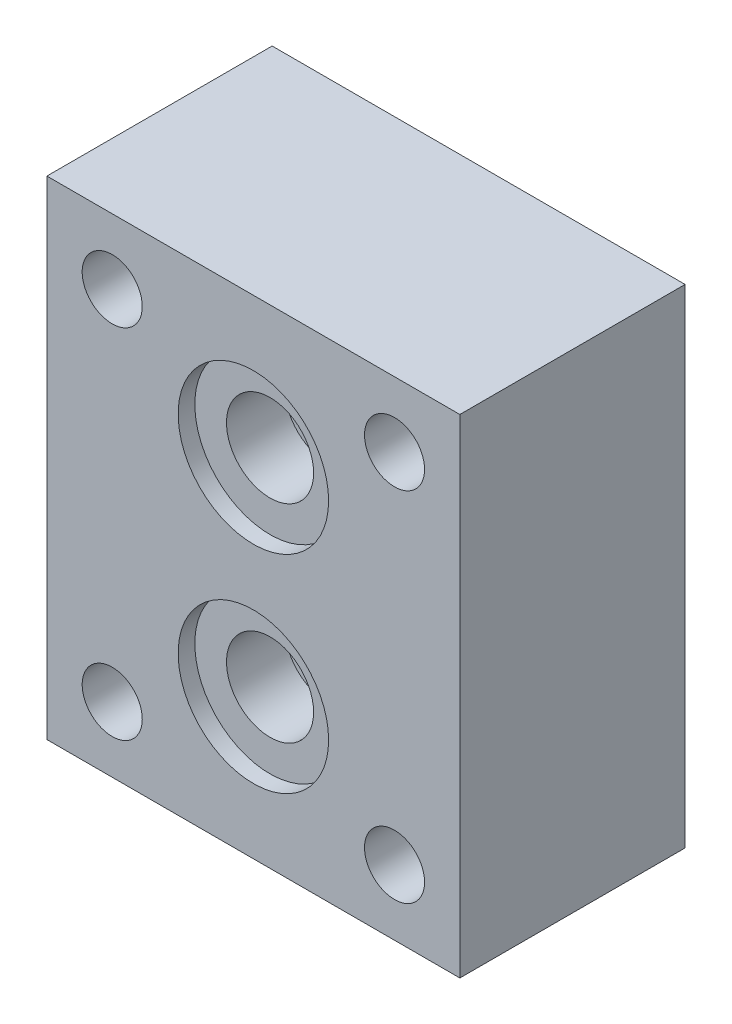
SolidWorks part; units mm, degrees
ref_plane "Front Plane" through (0, 0, 0) normal (1, 0, 0) x (0, 1, 0)
ref_plane "Top Plane" through (0, 0, 0) normal (0, 0, 1) x (0, 1, 0)
ref_plane "Right Plane" through (0, 0, 0) normal (0, 1, 0) x (-1, 0, 0)
sketch "Sketch1" plane through (0, 0, 0) normal (0, 0, 1) x (0, 1, 0)
  line L1 (-41.275, -34.925) -> (41.275, -34.925)
  line L2 (-41.275, -34.925) -> (-41.275, 34.925)
  line L3 (-41.275, 34.925) -> (41.275, 34.925)
  line L4 (41.275, -34.925) -> (41.275, 34.925)
  line L5 (-41.275, -34.925) -> (41.275, 34.925) construction
  line L6 (-41.275, 34.925) -> (41.275, -34.925) construction
  point P0 (0, 0)
  dimension "D1" = 41.275
  dimension "D2" = 34.925
extrude "Boss-Extrude1" add sketch "Sketch1" along normal mid plane 38.1
sketch "Sketch2" plane through (0, 0, 0) normal (0, 0, 1) x (0, 1, 0)
  circle A0 centre (-30.226, -23.876) radius 5.08
  circle A1 centre (30.226, -23.876) radius 5.08
  circle A2 centre (-30.226, 23.876) radius 5.08
  circle A3 centre (30.226, 23.876) radius 5.08
  point P8 (0, 0)
  dimension "D1" = 10.16
  dimension "D2" = 10.16
  dimension "D3" = 10.16
  dimension "D4" = 10.16
  dimension "D5" = 60.452
  dimension "D6" = 47.752
  dimension "D7" = 30.226
  dimension "D8" = 23.876
extrude "Cut-Extrude2" cut sketch "Sketch2" against normal through all from offset 19.05
sketch "Sketch3" plane through (0, 0, 0) normal (0, 0, 1) x (0, 1, 0)
  circle A0 centre (-17.526, 0) radius 7.366
  circle A1 centre (17.526, 0) radius 7.366
  point P4 (0, 0)
  dimension "D1" = 14.732
  dimension "D2" = 14.732
  dimension "D3" = 35.052
  dimension "D4" = 17.526
extrude "Cut-Extrude4" cut sketch "Sketch3" against normal blind 12.7 from offset 19.05
sketch "Sketch4" plane through (0, 0, 0) normal (0, 0, 1) x (0, 1, 0)
  circle A0 centre (-17.526, 0) radius 12.7254
  circle A1 centre (17.526, 0) radius 12.7254
  point P4 (0, 0)
  dimension "D1" = 25.4508
  dimension "D2" = 25.4508
  dimension "D3" = 35.052
  dimension "D4" = 17.526
extrude "Cut-Extrude6" cut sketch "Sketch4" against normal blind 2.8194 from offset 19.05
